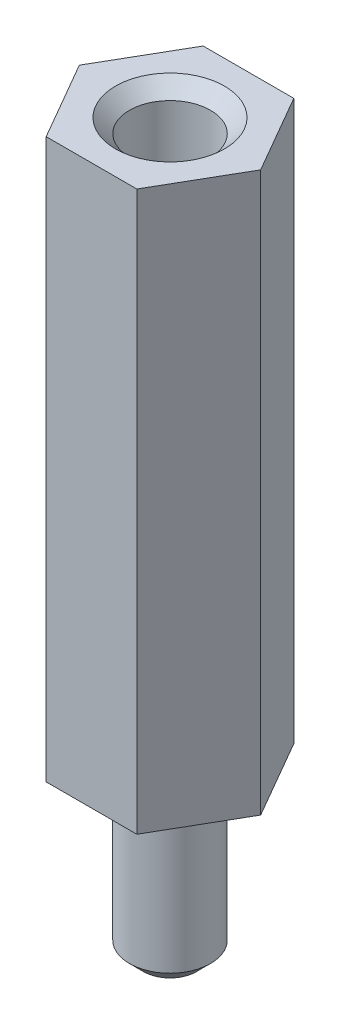
SolidWorks part; units mm, degrees
ref_plane "Front Plane" through (0, 0, 0) normal (0, 0, 1) x (1, 0, 0)
ref_plane "Top Plane" through (0, 0, 0) normal (0, 1, 0) x (1, 0, 0)
ref_plane "Right Plane" through (0, 0, 0) normal (1, 0, 0) x (0, 0, -1)
sketch "Sketch1" plane through (0, 0, 0) normal (0, 1, 0) x (1, 0, 0)
  line L1 (3.2447, 0) -> (1.6224, 2.81)
  line L2 (1.6224, 2.81) -> (-1.6224, 2.81)
  line L3 (-1.6224, 2.81) -> (-3.2447, 0)
  line L4 (-3.2447, 0) -> (-1.6224, -2.81)
  line L5 (-1.6224, -2.81) -> (1.6224, -2.81)
  line L6 (1.6224, -2.81) -> (3.2447, 0)
  circle A0 centre (0, 0) radius 2.81 construction
  dimension "D1" = 5.62
extrude "Boss-Extrude1" add sketch "Sketch1" along normal blind 20
sketch "Sketch2" plane through (0, 0, 0) normal (0, -1, 0) x (1, 0, 0)
  circle A0 centre (0, 0) radius 1.45
  dimension "D1" = 2.9
extrude "Boss-Extrude2" add sketch "Sketch2" along normal blind 6
sketch "Sketch3" plane through (0, 20, 0) normal (0, 1, 0) x (1, 0, 0)
  circle A0 centre (0, 0) radius 1.45
  circle A1 centre (0, 0) radius 1.45 construction
extrude "Cut-Extrude1" cut sketch "Sketch3" against normal blind 5
chamfer "Chamfer1" distance 0.5 angle 45 2 edges at (0, -6, -1.45) (0, 20, 1.45)
